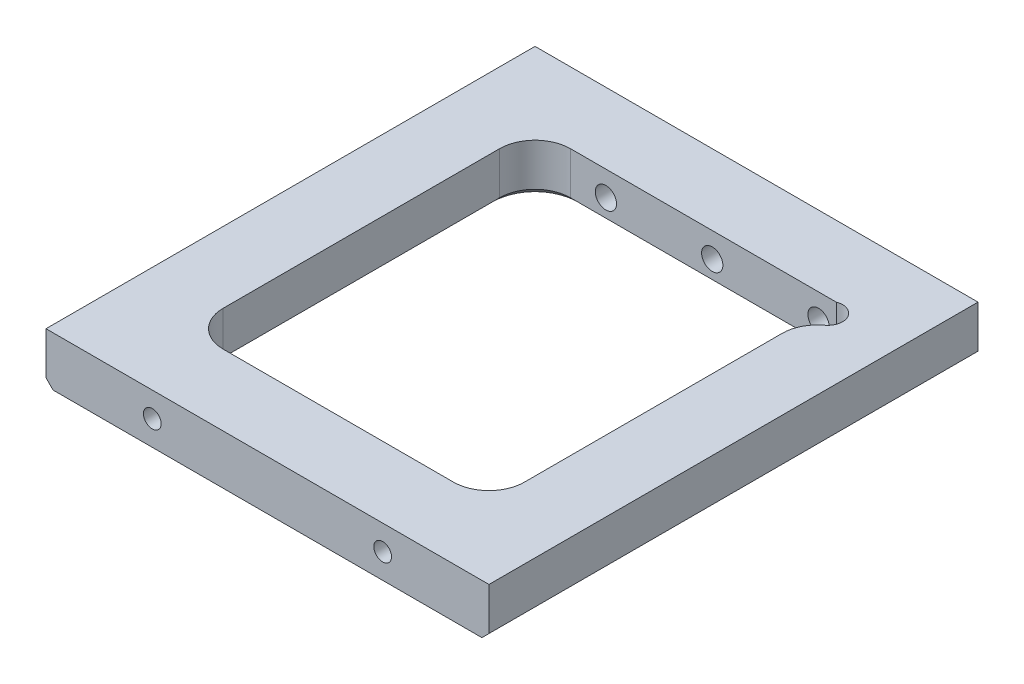
SolidWorks part; units mm, degrees
ref_plane "Front Plane" through (0, 0, 0) normal (0, 0, 1) x (1, 0, 0)
ref_plane "Top Plane" through (0, 0, 0) normal (0, 1, 0) x (1, 0, 0)
ref_plane "Right Plane" through (0, 0, 0) normal (1, 0, 0) x (0, 0, -1)
sketch "Sketch1" plane through (0, 0, 0) normal (0, 0, 1) x (1, 0, 0)
  line L1 (-125, 225) -> (-125, 185) construction
  line L7 (-125, 202.5) -> (-125, 197.5) construction
  line L8 (-125, 202.5) -> (-125, 197.5)
  line L9 (-125, 197.5) -> (-125, 193)
  line L10 (-125, 202.5) -> (-125, 207)
  line L11 (-125, 193) -> (0, 193)
  line L12 (0, -225) -> (0, 225) construction
  line L13 (-125, 207) -> (0, 207)
  line L14 (0, 207) -> (0, 193)
extrude "Boss-Extrude1" add sketch "Sketch1" along normal offset from surface (138 mm away) 12
sketch "Sketch3" plane through (0, 207, 0) normal (0, 1, 0) x (1, 0, 0)
  line L22 (-105, -20) -> (-105, -118)
  line L23 (-105, -118) -> (-20, -118)
  line L24 (-20, -118) -> (-20, -20)
  line L25 (-20, -20) -> (-105, -20)
  line L26 (-105, -30) -> (-105, -108)
  line L27 (-95, -118) -> (-30, -118)
  line L28 (-20, -108) -> (-20, -35.2972)
  line L29 (-20, -20) -> (-95, -20)
  arc A1 (-15.9861, -27.2867) -> (-20, -20) centre (-18.5, -23.9226) ccw
  arc A2 (-20, -35.2972) -> (-15.9861, -27.2867) centre (-10, -35.2972) cw
  arc A3 (-95, -20) -> (-105, -30) centre (-95, -30) ccw
  arc A4 (-105, -108) -> (-95, -118) centre (-95, -108) ccw
  arc A5 (-30, -118) -> (-20, -108) centre (-30, -108) ccw
  dimension "D2" = 10
  dimension "D3" = 10
  dimension "D1" = 20
extrude "Cut-Extrude1" cut sketch "Sketch3" against normal through all
sketch "Sketch5" plane through (0, 0, 20) normal (0, 0, 1) x (1, 0, 0)
  circle A0 centre (-85, 200) radius 3 construction
  circle A1 centre (-55, 200) radius 3 construction
  circle A2 centre (-25, 200) radius 3 construction
  circle A3 centre (-85, 200) radius 3
  circle A4 centre (-55, 200) radius 3
  circle A5 centre (-25, 200) radius 3
hole_wizard "Ø6.0mm Dowel Hole1" positions "Sketch6" profile "Sketch7" hole size "Ø6.0" standard "ANSI Metric"
sketch "Sketch6" plane through (0, 0, 20) normal (0, 0, 1) x (1, 0, 0)
  point P0 (-25, 200)
  point P3 (-55, 200)
  point P6 (-85, 200)
sketch "Sketch7" plane through (-25, 200, 20) normal (1, 0, 0) x (0, -1, 0)
  line L0 (0, 0) -> (0, 30)
  line L1 (0, 30) -> (3, 28.1974)
  line L2 (3, 28.1974) -> (3, 0)
  line L5 (3, 0) -> (0, 0)
  line L10 (0, 30) -> (-3, 28.1974) construction
  line L11 (0, -6.35) -> (0, 107.95) construction
  dimension "Hole Dia." = 6
  dimension "Hole Depth" = 30
  dimension "Drill Angle" = 118
sketch "Sketch8" plane through (0, 0, 138) normal (0, 0, 1) x (1, 0, 0)
  line L0 (0, 200) -> (-30, 200)
  line L1 (0, 207) -> (0, 193) construction
  line L2 (-125, 200) -> (-95, 200)
  line L3 (-125, 193) -> (-125, 207) construction
hole_wizard "M6x1.0 Tapped Hole1" positions "Sketch9" profile "Sketch10" tap size "M6x1.0" standard "ANSI Metric"
sketch "Sketch9" plane through (0, 0, 138) normal (0, 0, 1) x (1, 0, 0)
  point P0 (-95, 200)
  point P3 (-30, 200)
sketch "Sketch10" plane through (-95, 200, 138) normal (1, 0, 0) x (0, -1, 0)
  line L0 (0, 0) -> (0, 23)
  line L1 (0, 23) -> (2.5, 21.4978)
  line L2 (2.5, 21.4978) -> (2.5, 0)
  line L5 (2.5, 0) -> (0, 0)
  line L10 (0, 23) -> (-2.5, 21.4978) construction
  line L11 (0, -6.35) -> (0, 107.95) construction
  dimension "Tap Drill Dia." = 5
  dimension "Tap Drill Depth" = 23
  dimension "Drill Angle" = 118
cosmetic thread "Hole Thread1" parameters "D1"=20, "D2"=6
cosmetic thread "Hole Thread2" parameters "D1"=20, "D2"=6
chamfer "Chamfer1" distance 2 angle 45 11 edges at (0, 193, 69) (-125, 193, 69) (-14.8215, 193, 21.8963) (-18.9404, 193, 30.8172) (-20, 193, 71.6486) (-22.9289, 193, 115.0711) (-57.5, 193, 20) (-62.5, 193, 118) (-102.0711, 193, 22.9289) (-102.0711, 193, 115.0711) (-105, 193, 69)
